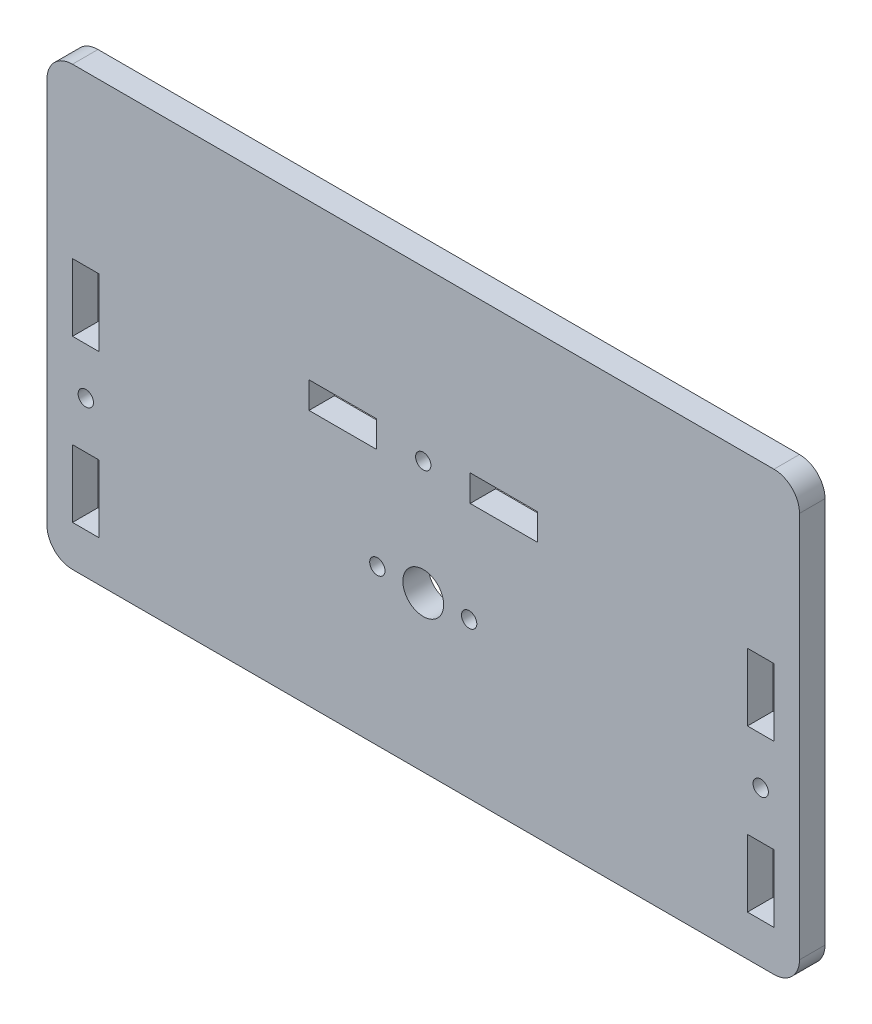
SolidWorks part; units mm, degrees
ref_plane "Front" through (0, 0, 0) normal (0, 0, 1) x (1, 0, 0)
ref_plane "Top" through (0, 0, 0) normal (0, 1, 0) x (1, 0, 0)
ref_plane "Right" through (0, 0, 0) normal (1, 0, 0) x (0, 0, -1)
sketch "Sketch1" plane through (0, 0, 0) normal (0, 0, 1) x (1, 0, 0)
  line L0 (-6.2321, 97.3106) -> (-143.765, 97.3106)
  line L1 (-1.2321, 92.3106) -> (-1.2321, 16.5106)
  line L2 (-6.235, 19.5106) -> (-11.435, 19.5106)
  line L3 (-11.435, 19.5106) -> (-11.435, 32.7106)
  line L4 (-11.435, 51.1106) -> (-11.435, 64.3106)
  line L5 (-6.235, 64.3106) -> (-6.235, 51.1106)
  line L6 (-6.235, 32.7106) -> (-11.435, 32.7106)
  line L7 (-6.235, 32.7106) -> (-6.235, 19.5106)
  line L8 (-6.235, 64.3106) -> (-11.435, 64.3106)
  line L9 (-6.235, 51.1106) -> (-11.435, 51.1106)
  line L10 (-8.835, 41.9106) -> (-1.2321, 41.9106) construction
  line L11 (-8.835, 32.7106) -> (-8.835, 51.1106) construction
  line L12 (-148.765, 92.3106) -> (-148.765, 16.5106)
  line L13 (-74.9985, 97.3106) -> (-74.9985, 64.3106) construction
  line L14 (-52.5985, 66.9106) -> (-52.5985, 61.7106)
  line L15 (-52.5985, 61.7106) -> (-65.7985, 61.7106)
  line L16 (-84.1985, 61.7106) -> (-97.3985, 61.7106)
  line L17 (-97.3985, 66.9106) -> (-84.1985, 66.9106)
  line L18 (-143.765, 11.5106) -> (-6.2321, 11.5106)
  line L19 (-65.7985, 66.9106) -> (-65.7985, 61.7106)
  line L20 (-65.7985, 66.9106) -> (-52.5985, 66.9106)
  line L21 (-97.3985, 66.9106) -> (-97.3985, 61.7106)
  line L22 (-84.1985, 66.9106) -> (-84.1985, 61.7106)
  line L24 (-141.162, 32.7106) -> (-141.162, 51.1106) construction
  line L26 (-65.7985, 64.3106) -> (-84.1985, 64.3106) construction
  line L27 (-143.762, 51.1106) -> (-138.562, 51.1106)
  line L28 (-143.762, 64.3106) -> (-138.562, 64.3106)
  line L29 (-143.762, 32.7106) -> (-143.762, 19.5106)
  line L30 (-143.762, 32.7106) -> (-138.562, 32.7106)
  line L31 (-143.762, 64.3106) -> (-143.762, 51.1106)
  line L32 (-138.562, 51.1106) -> (-138.562, 64.3106)
  line L33 (-138.562, 19.5106) -> (-138.562, 32.7106)
  line L34 (-143.762, 19.5106) -> (-138.562, 19.5106)
  circle A0 centre (-74.9985, 41.9106) radius 4
  circle A1 centre (-83.9985, 41.9106) radius 1.5
  circle A2 centre (-65.9985, 41.9106) radius 1.5
  circle A3 centre (-8.835, 41.9106) radius 1.5
  arc A4 (-143.765, 97.3106) -> (-148.765, 92.3106) centre (-143.765, 92.3106) ccw
  circle A5 centre (-141.162, 41.9106) radius 1.5
  arc A6 (-148.765, 16.5106) -> (-143.765, 11.5106) centre (-143.765, 16.5106) ccw
  arc A7 (-6.2321, 11.5106) -> (-1.2321, 16.5106) centre (-6.2321, 16.5106) ccw
  arc A8 (-6.2321, 97.3106) -> (-1.2321, 92.3106) centre (-6.2321, 92.3106) cw
  circle A9 centre (-74.9985, 64.3106) radius 1.5
extrude "Boss-Extrude1" add sketch "Sketch1" along normal blind 5
